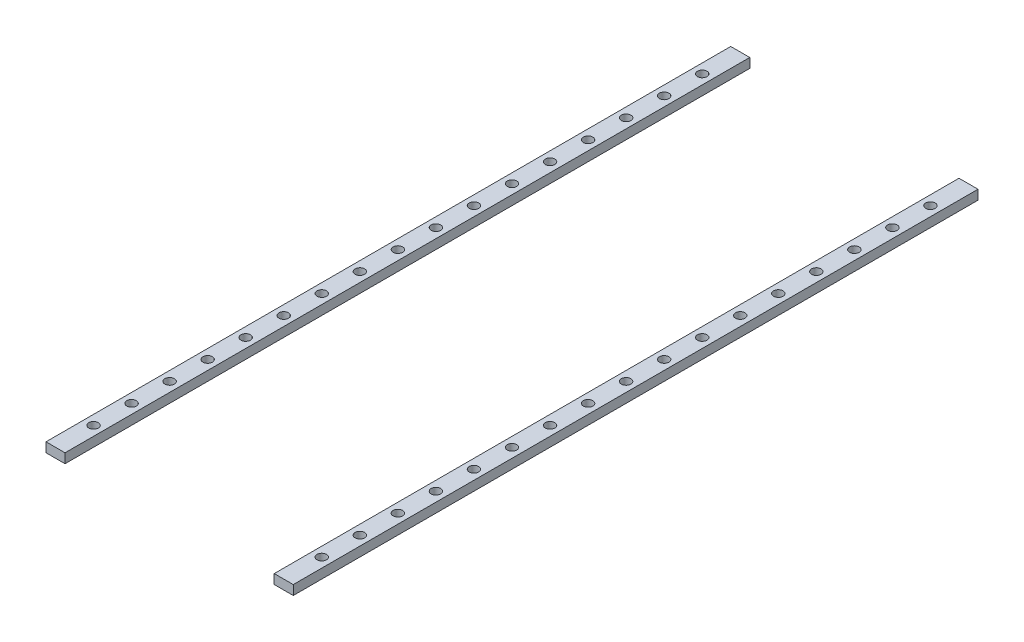
SolidWorks part; units mm, degrees
ref_plane "Front Plane" through (0, 0, 0) normal (0, 0, 1) x (1, 0, 0)
ref_plane "Top Plane" through (0, 0, 0) normal (0, 1, 0) x (1, 0, 0)
ref_plane "Right Plane" through (0, 0, 0) normal (1, 0, 0) x (0, 0, -1)
sketch "Sketch1" plane through (0, 0, 0) normal (0, 1, 0) x (1, 0, 0)
  line L0 (0, 0) -> (0, 914.4) construction
  line L1 (0, 914.4) -> (152.4, 914.4) construction
  line L2 (152.4, 0) -> (152.4, 50.8) construction
  line L3 (152.4, 914.4) -> (165.1, 914.4)
  line L4 (152.4, 914.4) -> (139.7, 914.4)
  line L5 (139.7, 914.4) -> (139.7, 0)
  line L6 (139.7, 0) -> (165.1, 0)
  line L7 (165.1, 0) -> (165.1, 914.4)
  line L8 (-152.4, 0) -> (-152.4, 50.8) construction
  line L9 (-165.1, 0) -> (-165.1, 914.4)
  line L10 (-139.7, 0) -> (-165.1, 0)
  line L11 (-139.7, 914.4) -> (-139.7, 0)
  line L12 (-152.4, 914.4) -> (-139.7, 914.4)
  line L13 (-152.4, 914.4) -> (-165.1, 914.4)
  circle A0 centre (152.4, 50.8) radius 6.35
  circle A1 centre (152.4, 101.6) radius 6.35
  circle A2 centre (152.4, 152.4) radius 6.35
  circle A3 centre (152.4, 203.2) radius 6.35
  circle A4 centre (152.4, 254) radius 6.35
  circle A5 centre (152.4, 304.8) radius 6.35
  circle A6 centre (152.4, 355.6) radius 6.35
  circle A7 centre (152.4, 406.4) radius 6.35
  circle A8 centre (152.4, 457.2) radius 6.35
  circle A9 centre (152.4, 508) radius 6.35
  circle A10 centre (152.4, 558.8) radius 6.35
  circle A11 centre (152.4, 609.6) radius 6.35
  circle A12 centre (152.4, 660.4) radius 6.35
  circle A13 centre (152.4, 711.2) radius 6.35
  circle A14 centre (152.4, 762) radius 6.35
  circle A15 centre (152.4, 812.8) radius 6.35
  circle A16 centre (152.4, 863.6) radius 6.35
  circle A17 centre (-152.4, 863.6) radius 6.35
  circle A18 centre (-152.4, 812.8) radius 6.35
  circle A19 centre (-152.4, 762) radius 6.35
  circle A20 centre (-152.4, 711.2) radius 6.35
  circle A21 centre (-152.4, 660.4) radius 6.35
  circle A22 centre (-152.4, 609.6) radius 6.35
  circle A23 centre (-152.4, 558.8) radius 6.35
  circle A24 centre (-152.4, 508) radius 6.35
  circle A25 centre (-152.4, 457.2) radius 6.35
  circle A26 centre (-152.4, 406.4) radius 6.35
  circle A27 centre (-152.4, 355.6) radius 6.35
  circle A28 centre (-152.4, 304.8) radius 6.35
  circle A29 centre (-152.4, 254) radius 6.35
  circle A30 centre (-152.4, 203.2) radius 6.35
  circle A31 centre (-152.4, 152.4) radius 6.35
  circle A32 centre (-152.4, 101.6) radius 6.35
  circle A33 centre (-152.4, 50.8) radius 6.35
  dimension "D1" = 152.4
  dimension "D2" = 914.4
  dimension "D3" = 12.7
  dimension "D4" = 12.7
  dimension "D5" = 50.8
extrude "Boss-Extrude1" add sketch "Sketch1" along normal blind 12.7
